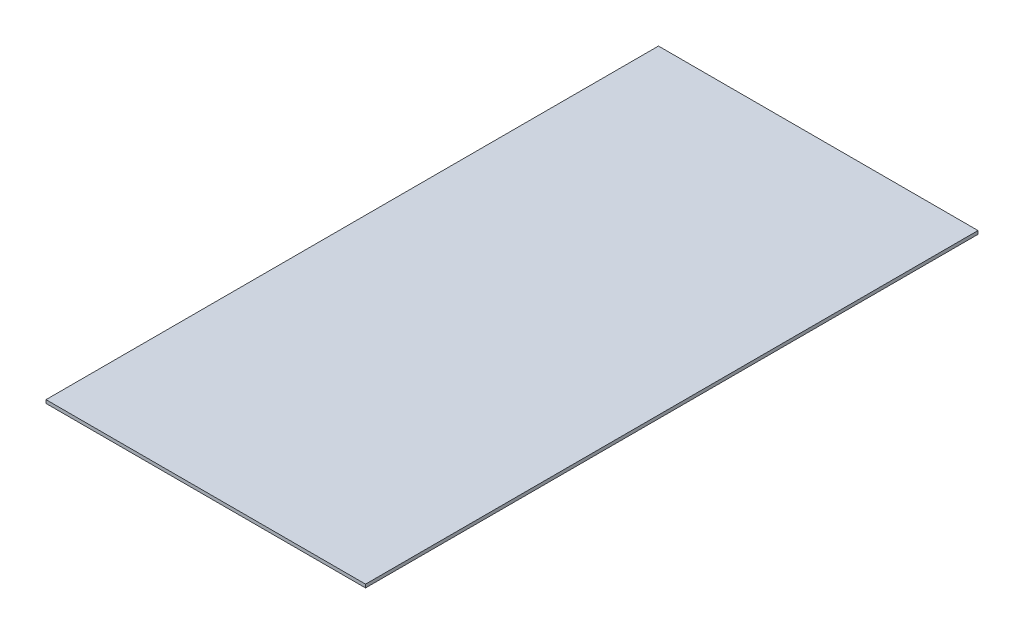
SolidWorks part; units mm, degrees
ref_plane "Front Plane" through (0, 0, 0) normal (0, 0, 1) x (1, 0, 0)
ref_plane "Top Plane" through (0, 0, 0) normal (0, 1, 0) x (1, 0, 0)
ref_plane "Right Plane" through (0, 0, 0) normal (1, 0, 0) x (0, 0, -1)
sketch "Sketch1" plane through (0, 0, 0) normal (0, 1, 0) x (1, 0, 0)
  line L1 (152.4, -292.1) -> (-152.4, -292.1)
  line L2 (152.4, -292.1) -> (152.4, 292.1)
  line L3 (152.4, 292.1) -> (-152.4, 292.1)
  line L4 (-152.4, -292.1) -> (-152.4, 292.1)
  line L5 (152.4, -292.1) -> (-152.4, 292.1) construction
  line L6 (152.4, 292.1) -> (-152.4, -292.1) construction
  point P0 (0, 0)
  dimension "D1" = 304.8
  dimension "D2" = 584.2
extrude "Boss-Extrude1" add sketch "Sketch1" along normal mid plane 3.175 contours L3 L4 L1 L2
